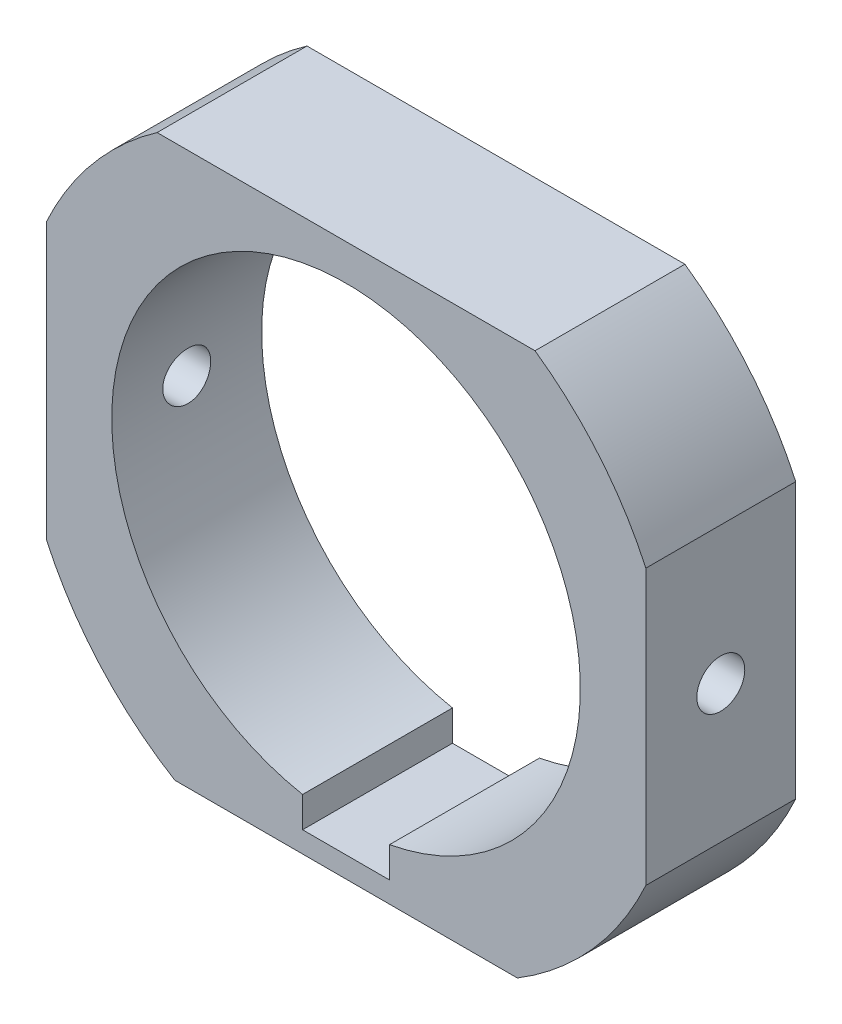
SolidWorks part; units mm, degrees
ref_plane "Front Plane" through (0, 0, 0) normal (0, 0, 1) x (1, 0, 0)
ref_plane "Top Plane" through (0, 0, 0) normal (0, 1, 0) x (1, 0, 0)
ref_plane "Right Plane" through (0, 0, 0) normal (1, 0, 0) x (0, 0, -1)
sketch "Sketch1" plane through (0, 0, 0) normal (0, 0, 1) x (1, 0, 0)
  line L1 (-6.3032, 9.015) -> (6.3032, 9.015)
  line L2 (11, 0) -> (-11, 0) construction
  line L3 (-4.7948, -9.9) -> (4.7948, -9.9)
  line L5 (10, 4.5826) -> (10, -4.5826)
  line L7 (0, 11) -> (0, -11) construction
  line L8 (-10, 4.5826) -> (-10, -4.5826)
  line L9 (-1.25, -8.5) -> (1.25, -8.5)
  line L10 (1.25, -8.5) -> (1.25, -7.5117)
  line L11 (-1.25, -8.5) -> (-1.25, -7.7144)
  line L13 (1.45, -8.7) -> (1.45, -7.4757)
  line L14 (-1.45, -8.7) -> (1.45, -8.7)
  line L15 (-1.45, -8.7) -> (-1.45, -7.6793)
  line L16 (-1.45, -8.7) -> (-1.45, -7.7144) construction
  line L17 (1.45, -8.7) -> (1.45, -7.5117) construction
  circle A0 centre (0, 0) radius 7.715
  circle A2 centre (0, 0) radius 7.815
  circle A3 centre (0, 0) radius 11
  dimension "D2" = 1.2
  dimension "D4" = 1.2
  dimension "D1" = 0.1
  dimension "D3" = 0.2
extrude "Boss-Extrude1" add sketch "Sketch1" along normal blind 5
sketch "Sketch2" plane through (0, 0, 0) normal (1, 0, 0) x (0, 0, -1)
  line L0 (-5, -4.5826) -> (-5, -9.9) construction
  line L1 (0, -9.9) -> (-5, -9.9)
  line L3 (0, -9.9) -> (0, -9.4)
  line L5 (0, -9.4) -> (-5, -9.4)
  line L6 (-5, -9.9) -> (-5, -9.4)
  line L7 (0, -9.9) -> (-5, -9.4) construction
  line L8 (0, -9.4) -> (-5, -9.9) construction
  point P4 (-2.5, -9.65)
  dimension "D1" = 0.5
extrude "Cut-Extrude1" cut sketch "Sketch2" against normal through all and the other way through all
sketch "Sketch3" plane through (10, 0, 0) normal (1, 0, 0) x (0, 0, -1)
  line L0 (-2.5, 4.5826) -> (-2.5, -4.5826) construction
  line L1 (-5, 4.5826) -> (0, 4.5826) construction
  line L2 (-5, -4.5826) -> (0, -4.5826) construction
  line L3 (-5, 0) -> (0, 0) construction
  line L4 (-5, 4.5826) -> (-5, -4.5826) construction
  circle A0 centre (-2.5, 0) radius 0.8
  dimension "D1" = 1.6
extrude "Cut-Extrude2" cut sketch "Sketch3" against normal through all
